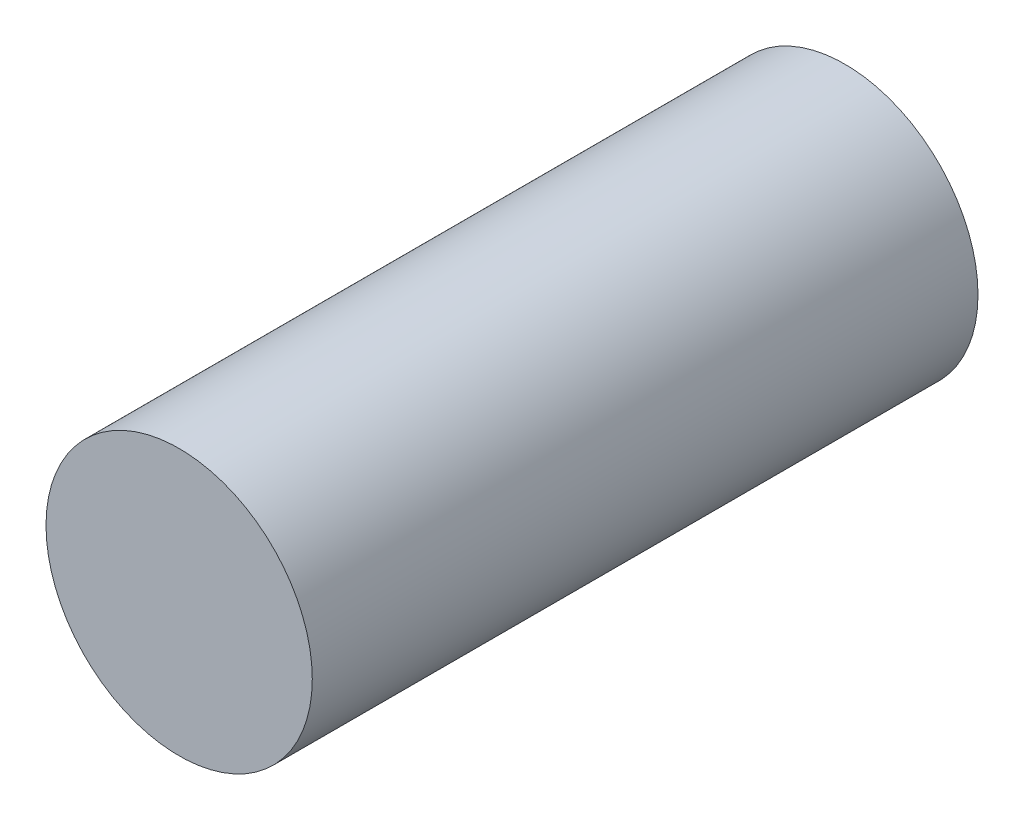
SolidWorks part; units mm, degrees
material "AISI 304"
ref_plane "Piano frontale" through (0, 0, 0) normal (0, 0, 1) x (1, 0, 0)
ref_plane "Piano superiore" through (0, 0, 0) normal (0, 1, 0) x (1, 0, 0)
ref_plane "Piano destro" through (0, 0, 0) normal (1, 0, 0) x (0, 0, -1)
sketch "Schizzo1" plane through (0, 0, 0) normal (0, 0, 1) x (1, 0, 0)
  circle A0 centre (0, 0) radius 4
  dimension "D1" = 8
extrude "Estrusione-Estrusione1" add sketch "Schizzo1" along normal blind 20
